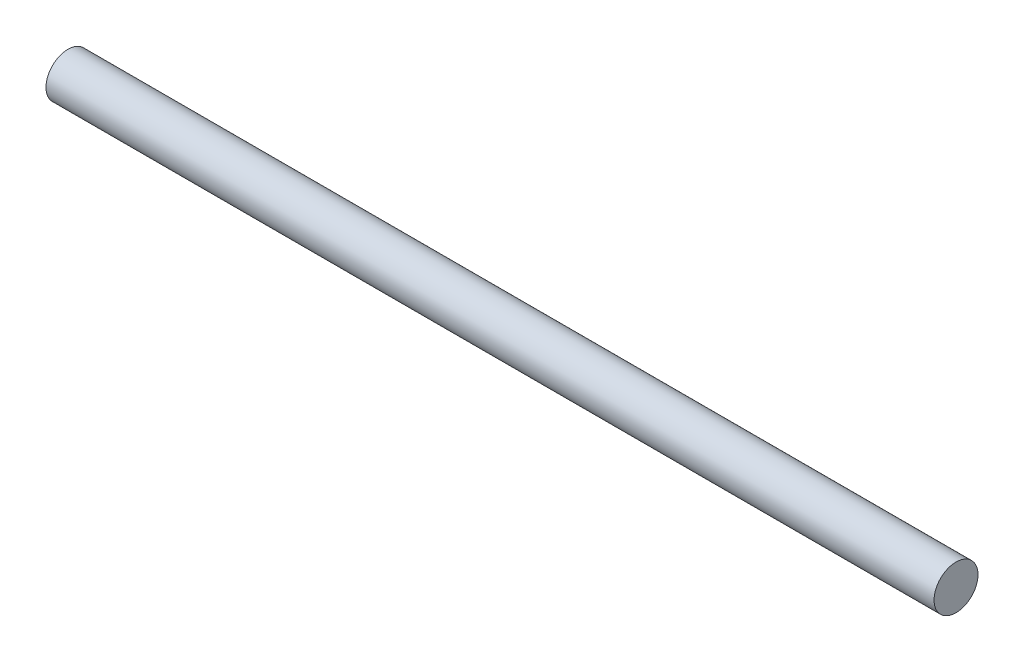
SolidWorks part; units mm, degrees
ref_plane "Plan de face" through (0, 0, 0) normal (0, 0, 1) x (1, 0, 0)
ref_plane "Plan de dessus" through (0, 0, 0) normal (0, 1, 0) x (1, 0, 0)
ref_plane "Plan de droite" through (0, 0, 0) normal (1, 0, 0) x (0, 0, -1)
sketch "Esquisse1" plane through (0, 0, 0) normal (1, 0, 0) x (0, 0, -1)
  circle A0 centre (0, 0) radius 2.5
  dimension "D1" = 5
extrude "Boss.-Extru.1" add sketch "Esquisse1" along normal blind 101
